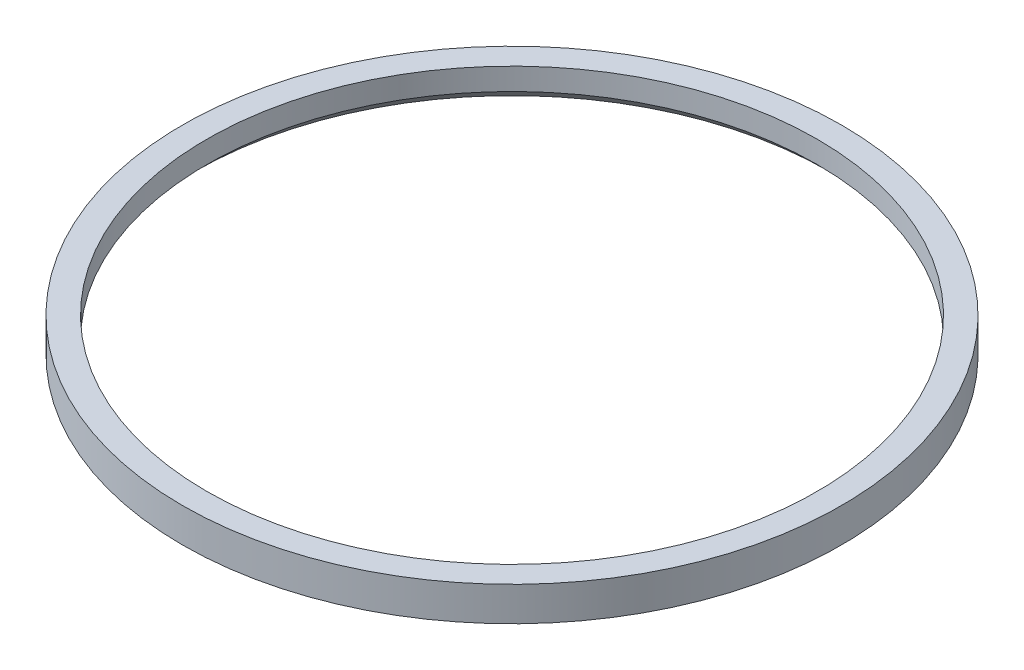
SolidWorks part; units mm, degrees
ref_plane "Front Plane" through (0, 0, 0) normal (0, 0, 1) x (1, 0, 0)
ref_plane "Top Plane" through (0, 0, 0) normal (0, 1, 0) x (1, 0, 0)
ref_plane "Right Plane" through (0, 0, 0) normal (1, 0, 0) x (0, 0, -1)
sketch "Sketch1" plane through (0, 0, 0) normal (0, 0, 1) x (1, 0, 0)
  line L0 (0, 0) -> (0, 99.0923) construction
  line L1 (13, 0.5146) -> (12.5, 1.0146)
  line L2 (12.5, 1.0146) -> (12.5, 1.9146)
  line L3 (12.5, 1.9146) -> (13.5, 1.9146)
  line L4 (13.5, 1.9146) -> (13.5, 0.5146)
  line L5 (13.5, 0.5146) -> (13, 0.5146)
  dimension "D1" = 135
  dimension "D2" = 0.5
  dimension "D3" = 1
  dimension "D4" = 1.4
  dimension "D5" = 13.5
revolve "Revolve1" add sketch "Sketch1" angle 360 about L0
